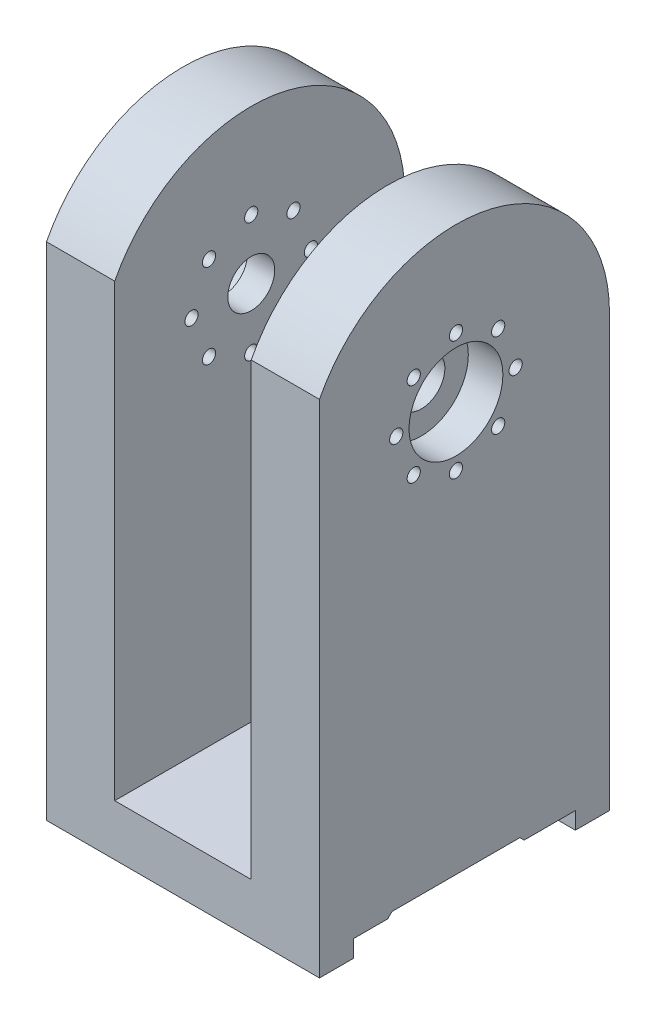
SolidWorks part; units mm, degrees
material "6061 Alloy"
ref_plane "Front Plane" through (0, 0, 0) normal (0, 0, 1) x (1, 0, 0)
ref_plane "Top Plane" through (0, 0, 0) normal (0, 1, 0) x (1, 0, 0)
ref_plane "Right Plane" through (0, 0, 0) normal (1, 0, 0) x (0, 0, -1)
sketch "Sketch1" plane through (0, 0, 0) normal (1, 0, 0) x (0, 0, -1)
  line L2 (107.95, 160.3375) -> (107.95, 0)
  line L3 (107.95, 0) -> (95.25, 0)
  line L4 (95.25, 0) -> (95.25, 6.35)
  line L5 (95.25, 6.35) -> (76.2, 6.35)
  line L6 (76.2, 6.35) -> (74.6125, 7.9375)
  line L7 (74.6125, 7.9375) -> (26.9875, 7.9375)
  line L8 (26.9875, 7.9375) -> (25.4, 6.35)
  line L9 (25.4, 6.35) -> (12.7, 6.35)
  line L10 (12.7, 6.35) -> (12.7, 0)
  line L11 (12.7, 0) -> (0, 0)
  line L12 (0, 0) -> (0, 186.5192)
  line L14 (50.8, 7.9375) -> (50.8, 160.3375) construction
  arc A4 (107.95, 160.3375) -> (0, 186.5192) centre (50.8, 160.3375) ccw
  dimension "D8" = 152.4
  dimension "D7" = 12.7
  dimension "D1" = 6.35
  dimension "D2" = 1.5875
  dimension "D3" = 12.7
  dimension "D4" = 12.7
  dimension "D5" = 6.35
  dimension "D6" = 19.05
  dimension "D9" = 107.95
extrude "Boss-Extrude1" add sketch "Sketch1" along normal blind 101.6
sketch "Sketch2" plane through (0, 0, -107.95) normal (0, 0, -1) x (-1, 0, 0)
  line L0 (-76.2, 98.425) -> (-76.2, 19.05)
  line L1 (-25.4, 19.05) -> (-25.4, 264.5802)
  line L2 (-76.2, 19.05) -> (-25.4, 19.05)
  line L4 (-101.6, 0) -> (-101.6, 160.3375) construction
  line L5 (-101.6, 0) -> (0, 0) construction
  line L6 (-76.2, 98.425) -> (-76.2, 264.5802)
  line L7 (-76.2, 264.5802) -> (-25.4, 264.5802)
  line L9 (0, 0) -> (0, 160.3375) construction
  dimension "D1" = 25.4
  dimension "D2" = 25.4
  dimension "D3" = 19.05
extrude "Cut-Extrude1" cut sketch "Sketch2" against normal through all and the other way through all
sketch "Sketch5" plane through (0, 0, 0) normal (-1, 0, 0) x (0, 0, 1)
  circle A0 centre (-50.8, 160.3375) radius 17.4625
  arc A1 (0, 186.5192) -> (-107.95, 160.3375) centre (-50.8, 160.3375) ccw construction
  dimension "D1" = 34.925
extrude "Cut-Extrude4" cut sketch "Sketch5" against normal blind 15.24
sketch "Sketch6" plane through (0, 0, 0) normal (-1, 0, 0) x (0, 0, 1)
  circle A0 centre (-50.8, 160.3375) radius 8.7312
  arc A1 (0, 186.5192) -> (-107.95, 160.3375) centre (-50.8, 160.3375) ccw construction
  dimension "D1" = 17.4625
extrude "Cut-Extrude5" cut sketch "Sketch6" against normal through all both and the other way through all
sketch "Sketch7" plane through (101.6, 0, 0) normal (1, 0, 0) x (0, 0, -1)
  circle A0 centre (50.8, 160.3375) radius 17.4625
  arc A1 (107.95, 160.3375) -> (0, 186.5192) centre (50.8, 160.3375) ccw construction
  dimension "D1" = 34.925
extrude "Cut-Extrude6" cut sketch "Sketch7" against normal up to surface (12.8587 mm away)
ref_plane "Plane1" through (50.8, 0, 0) normal (-1, 0, 0) x (0, 0, 1)
hole_wizard "1/4-20 Tapped Hole1" positions "Sketch10" profile "Sketch11" tap size "1/4-20" standard "ANSI Inch"
sketch "Sketch10" plane through (0, 0, 0) normal (0, -1, 0) x (-1, 0, 0)
  point P0 (-19.05, 6.35)
  point P3 (-82.55, 6.35)
  point P6 (-82.55, 101.6)
  point P9 (-19.05, 101.6)
sketch "Sketch11" plane through (19.05, 0, -6.35) normal (1, 0, 0) x (0, 0, -1)
  line L0 (0, 0) -> (0, 18.0438)
  line L1 (0, 18.0438) -> (2.5527, 16.51)
  line L2 (2.5527, 16.51) -> (2.5527, 0)
  line L5 (2.5527, 0) -> (0, 0)
  line L10 (0, 18.0438) -> (-2.5527, 16.51) construction
  line L11 (0, -6.35) -> (0, 107.95) construction
  dimension "Tap Drill Dia." = 5.1054
  dimension "Tap Drill Depth" = 16.51
  dimension "Drill Angle" = 118
cosmetic thread "Hole Thread1" parameters "D1"=12.7, "D2"=6.35
cosmetic thread "Hole Thread2" parameters "D1"=12.7, "D2"=6.35
cosmetic thread "Hole Thread3" parameters "D1"=12.7, "D2"=6.35
cosmetic thread "Hole Thread4" parameters "D1"=12.7, "D2"=6.35
hole_wizard "#10-24 Tapped Hole1" positions "Sketch12" profile "Sketch13" tap size "#10-24" standard "ANSI Inch"
sketch "Sketch12" plane through (0, 0, -107.95) normal (0, 0, -1) x (-1, 0, 0)
  line L0 (-101.6, 0) -> (0, 0) construction
  line L1 (-101.6, 0) -> (-101.6, 160.3375) construction
  line L2 (0, 0) -> (0, 160.3375) construction
  point P0 (-71.12, 3.175)
  point P2 (-30.48, 3.175)
  dimension "D1" = 3.175
  dimension "D2" = 3.175
  dimension "D3" = 30.48
  dimension "D4" = 30.48
sketch "Sketch13" plane through (71.12, 3.175, -107.95) normal (1, 0, 0) x (0, 1, 0)
  line L0 (0, 0) -> (0, 16.0887)
  line L1 (0, 16.0887) -> (1.8986, 14.9479)
  line L2 (1.8986, 14.9479) -> (1.8986, 0)
  line L5 (1.8986, 0) -> (0, 0)
  line L10 (0, 16.0887) -> (-1.8987, 14.9479) construction
  line L11 (0, -6.35) -> (0, 107.95) construction
  dimension "Tap Drill Dia." = 3.7973
  dimension "Tap Drill Depth" = 14.9479
  dimension "Drill Angle" = 118
cosmetic thread "Hole Thread5" parameters "D1"=9.652, "D2"=4.826
cosmetic thread "Hole Thread6" parameters "D1"=9.652, "D2"=4.826
hole_wizard "1/4 (0.25) Diameter Hole1" positions "Sketch14" profile "Sketch15" hole size "1/4" standard "ANSI Inch" end condition through all
sketch "Sketch14" plane through (0, 19.05, 0) normal (0, 1, 0) x (1, 0, 0)
  point P0 (38.1, 50.8)
sketch "Sketch15" plane through (38.1, 19.05, -50.8) normal (1, 0, 0) x (0, 0, 1)
  line L0 (0, 0) -> (0, 19.05)
  line L1 (0, 19.05) -> (3.175, 19.05)
  line L2 (3.175, 19.05) -> (3.175, 0)
  line L5 (3.175, 0) -> (0, 0)
  line L11 (0, -6.35) -> (0, 107.95) construction
  dimension "Thru Hole Dia." = 6.35
  dimension "Thru Hole Depth" = 19.05
hole_wizard "#10 (0.1935) Diameter Hole1" positions "Sketch16" profile "Sketch17" hole size "#10" standard "ANSI Inch" end condition through all
sketch "Sketch16" plane through (0, 0, 0) normal (-1, 0, 0) x (0, 0, 1)
  point P0 (-50.8, 138.1125)
  point P3 (-35.0846, 144.6221)
  point P6 (-28.575, 160.3375)
  point P9 (-35.0846, 176.0529)
  point P12 (-50.8, 182.5625)
  point P15 (-66.5154, 176.0529)
  point P18 (-73.025, 160.3375)
  point P21 (-66.5154, 144.6221)
sketch "Sketch17" plane through (0, 138.1125, -50.8) normal (0, 1, 0) x (0, 0, 1)
  line L0 (0, 0) -> (0, 101.6)
  line L1 (0, 101.6) -> (2.4574, 101.6)
  line L2 (2.4574, 101.6) -> (2.4574, 0)
  line L5 (2.4574, 0) -> (0, 0)
  line L11 (0, -6.35) -> (0, 107.95) construction
  dimension "Thru Hole Dia." = 4.9149
  dimension "Thru Hole Depth" = 101.6
sketch "Sketch18" plane through (25.4, 0, 0) normal (1, 0, 0) x (0, 0, -1)
  line L0 (95.9347, 56.3251) -> (92.0605, 47.6236) construction
  line L1 (101.7357, 53.7424) -> (97.8615, 45.0409)
  line L2 (90.1337, 58.9079) -> (86.2595, 50.2064)
  line L3 (95.9347, 56.3251) -> (107.95, 83.312) construction
  line L4 (107.95, 160.3375) -> (107.95, 19.05) construction
  line L5 (0, 19.05) -> (107.95, 19.05) construction
  arc A0 (101.7357, 53.7424) -> (90.1337, 58.9079) centre (95.9347, 56.3251) ccw
  arc A1 (86.2595, 50.2064) -> (97.8615, 45.0409) centre (92.0605, 47.6236) ccw
  point P2 (93.9976, 51.9744)
  point P14 (93.9976, 51.9744)
  dimension "D1" = 66
  dimension "D2" = 83.312
  dimension "D3" = 12.7
  dimension "D4" = 9.525
extrude "Cut-Extrude7" cut sketch "Sketch18" against normal up to next
ref_plane "Plane2" through (0, 56.0097, -24.9371) normal (0, 0.9135, -0.4067) x (1, 0, 0)
hole_wizard "1/4-20 Tapped Hole2" positions "Sketch19" profile "Sketch20" tap size "1/4-20" standard "ANSI Inch"
sketch "Sketch19" plane through (0, 56.0097, -24.9371) normal (0, 0.9135, -0.4067) x (1, 0, 0)
  line L0 (25.4, -7.7483) -> (25.4, 90.8689) construction
  point P0 (31.75, 64.9155)
  dimension "D1" = 6.35
sketch "Sketch20" plane through (31.75, 29.6062, -84.2404) normal (1, 0, 0) x (0, 0.4067, 0.9135)
  line L0 (0, 0) -> (0, 18.0438)
  line L1 (0, 18.0438) -> (2.5527, 16.51)
  line L2 (2.5527, 16.51) -> (2.5527, 0)
  line L5 (2.5527, 0) -> (0, 0)
  line L10 (0, 18.0438) -> (-2.5527, 16.51) construction
  line L11 (0, -6.35) -> (0, 107.95) construction
  dimension "Tap Drill Dia." = 5.1054
  dimension "Tap Drill Depth" = 16.51
  dimension "Drill Angle" = 118
cosmetic thread "Hole Thread7" parameters "D1"=12.7, "D2"=6.35
